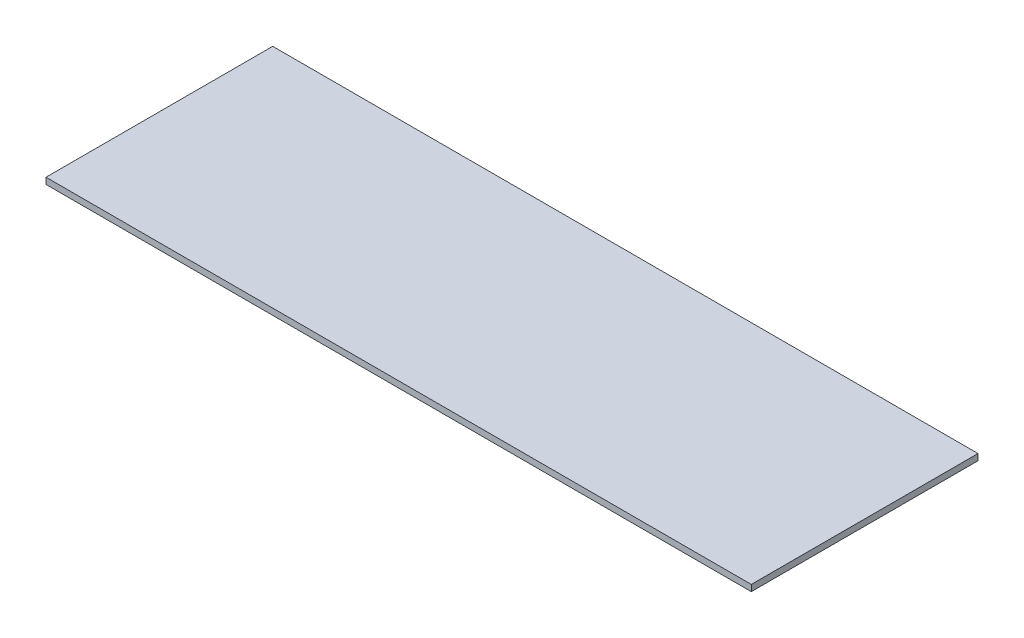
SolidWorks part; units mm, degrees
ref_plane "Front Plane" through (0, 0, 0) normal (0, 0, 1) x (1, 0, 0)
ref_plane "Top Plane" through (0, 0, 0) normal (0, 1, 0) x (1, 0, 0)
ref_plane "Right Plane" through (0, 0, 0) normal (1, 0, 0) x (0, 0, -1)
sketch "Sketch1" plane through (0, 0, 0) normal (0, 1, 0) x (1, 0, 0)
  line L1 (-355.6, -114.3) -> (355.6, -114.3)
  line L2 (-355.6, -114.3) -> (-355.6, 114.3)
  line L3 (-355.6, 114.3) -> (355.6, 114.3)
  line L4 (355.6, -114.3) -> (355.6, 114.3)
  line L5 (-355.6, -114.3) -> (355.6, 114.3) construction
  line L6 (-355.6, 114.3) -> (355.6, -114.3) construction
  point P0 (0, 0)
  dimension "D1" = 711.2
  dimension "D2" = 228.6
extrude "Boss-Extrude1" add sketch "Sketch1" along normal blind 6.35
